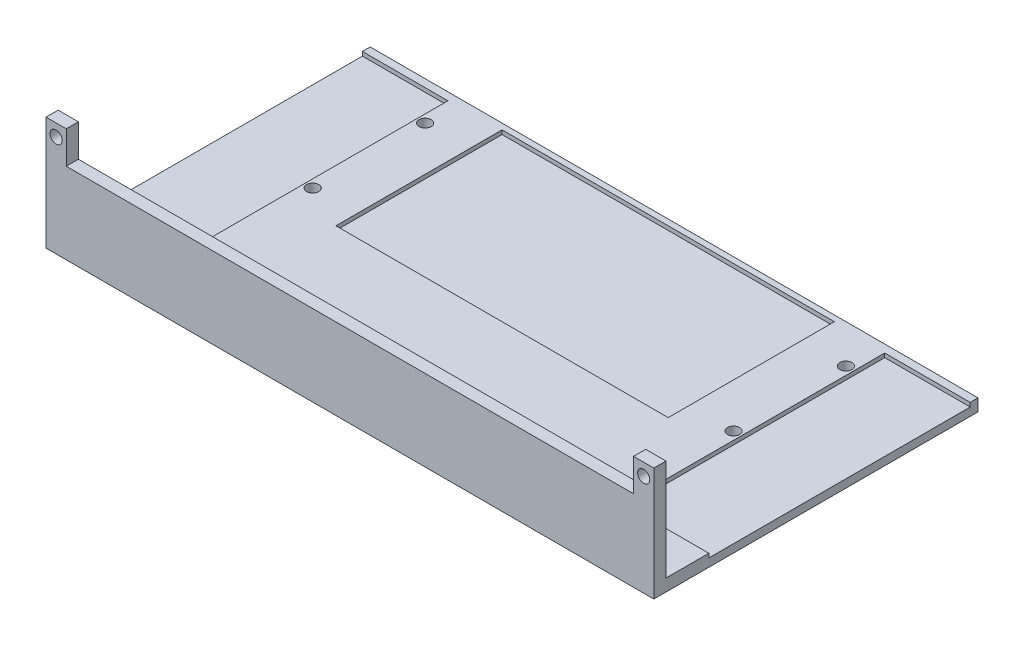
SolidWorks part; units mm, degrees
ref_plane "Front Plane" through (0, 0, 0) normal (0, 0, 1) x (1, 0, 0)
ref_plane "Top Plane" through (0, 0, 0) normal (0, 1, 0) x (1, 0, 0)
ref_plane "Right Plane" through (0, 0, 0) normal (1, 0, 0) x (0, 0, -1)
sketch "Sketch1" plane through (0, 0, 0) normal (1, 0, 0) x (0, 0, -1)
  line L0 (-62.7559, 0) -> (-62.7559, 28)
  line L1 (-62.7559, 28) -> (-59.7559, 28)
  line L2 (-59.7559, 28) -> (-59.7559, 3)
  line L3 (-62.7559, 0) -> (17.2441, 0)
  line L4 (17.2441, 0) -> (17.2441, 3)
  line L5 (17.2441, 3) -> (-59.7559, 3)
extrude "Boss-Extrude2" add sketch "Sketch1" against normal blind 150 contours L5 L2 L1 L0 L3 L4
ref_plane "Plane1" through (0, 3, -17.2441) normal (1, 0, 0) x (0, 0, -1)
sketch "Sketch4" plane through (0, 3, 0) normal (0, 1, 0) x (1, 0, 0)
  line L0 (-150, 15.3229) -> (-150, -49.1771)
  line L2 (0, 15.3229) -> (-21.1, 15.3229)
  line L3 (0, -24.0059) -> (0, 58.4941) construction
  line L4 (-21.1, 15.3229) -> (-21.1, -49.1771)
  line L5 (-21.1, -49.1771) -> (0, -49.1771)
  line L6 (0, 17.2441) -> (0, -59.7559) construction
  line L7 (0, -49.1771) -> (0, 15.3229)
  line L8 (-150, 17.2441) -> (-150, -59.7559) construction
  line L9 (-150, -49.1771) -> (-128.9, -49.1771)
  line L10 (-128.9, -49.1771) -> (-128.9, 15.3229)
  line L11 (-128.9, 15.3229) -> (-150, 15.3229)
extrude "Cut-Extrude1" cut sketch "Sketch4" against normal blind 1
sketch "Sketch5" plane through (0, 3, 0) normal (0, 1, 0) x (1, 0, 0)
  line L9 (-116, -25.2059) -> (-116, 15.7941)
  line L10 (-116, 15.7941) -> (-34, 15.7941)
  line L11 (-34, 15.7941) -> (-34, -25.2059)
  line L12 (-34, -25.2059) -> (-116, -25.2059)
extrude "Cut-Extrude2" cut sketch "Sketch5" against normal blind 1
sketch "Sketch6" plane through (0, 0, 62.7559) normal (0, 0, 1) x (1, 0, 0)
  line L0 (-150, 24.3465) -> (-145, 24.3465)
  line L1 (-150, 0) -> (-150, 28) construction
  line L2 (0, 22.6077) -> (-5, 22.6077)
  line L3 (0, 0) -> (0, 28) construction
  line L4 (-145, 28) -> (-145, 20)
  line L5 (-150, 28) -> (0, 28) construction
  line L6 (-145, 20) -> (-5, 20)
  line L7 (-5, 20) -> (-5, 28)
  line L8 (-5, 28) -> (-145, 28)
extrude "Cut-Extrude3" cut sketch "Sketch6" against normal blind 3 contours L8 L4 L6 L7
sketch "Sketch7" plane through (0, 0, 62.7559) normal (0, 0, 1) x (1, 0, 0)
  circle A1 centre (-2.5, 25) radius 1.5
  circle A2 centre (-147.5, 25) radius 1.5
extrude "Cut-Extrude4" cut sketch "Sketch7" against normal blind 3
sketch "Sketch8" plane through (0, 3, 0) normal (0, 1, 0) x (1, 0, 0)
  circle A0 centre (-23.1, -47.7559) radius 1.5
  circle A1 centre (-23.1, -20.0059) radius 1.5
  circle A2 centre (-23.1, 7.7441) radius 1.5
  circle A3 centre (-126.9341, -47.7559) radius 1.5
  circle A4 centre (-126.9341, -20.0059) radius 1.5
  circle A5 centre (-126.9341, 7.7441) radius 1.5
extrude "Cut-Extrude5" cut sketch "Sketch8" against normal blind 3
